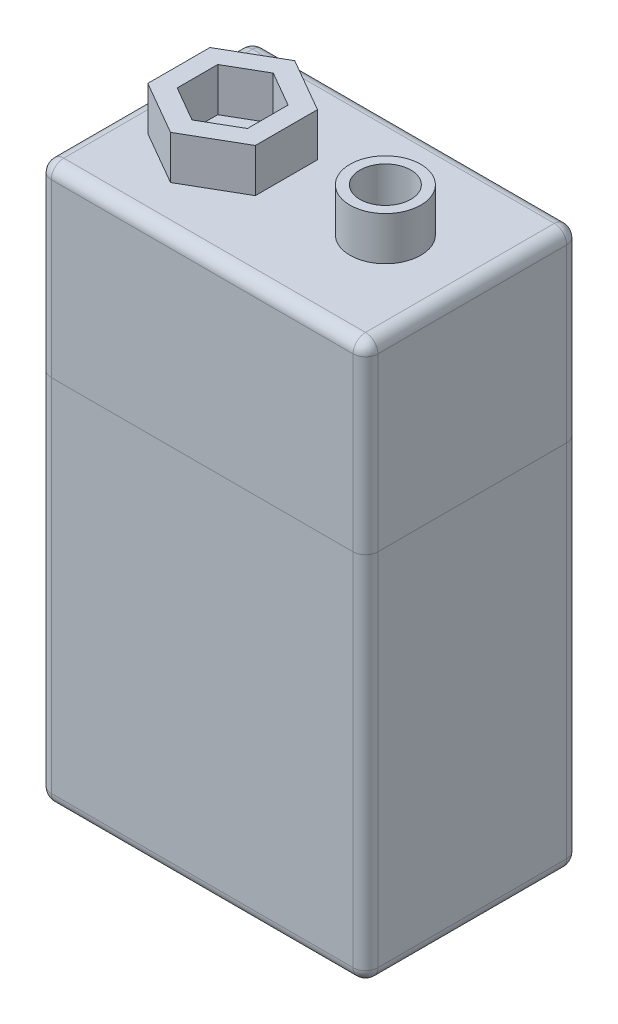
SolidWorks part; units mm, degrees
ref_plane "Alzado" through (0, 0, 0) normal (0, 0, 1) x (1, 0, 0)
ref_plane "Planta" through (0, 0, 0) normal (0, 1, 0) x (1, 0, 0)
ref_plane "Vista lateral" through (0, 0, 0) normal (1, 0, 0) x (0, 0, -1)
sketch "Croquis1" plane through (0, 0, 0) normal (0, 0, 1) x (1, 0, 0)
  line L1 (-13.15, 22.4) -> (13.15, 22.4)
  line L2 (-13.15, 22.4) -> (-13.15, -22.4)
  line L3 (-13.15, -22.4) -> (13.15, -22.4)
  line L4 (13.15, 22.4) -> (13.15, -22.4)
  line L5 (-13.15, 22.4) -> (13.15, -22.4) construction
  line L6 (-13.15, -22.4) -> (13.15, 22.4) construction
  point P0 (0, 0)
  dimension "D1" = 26.3
  dimension "D2" = 44.8
extrude "Saliente-Extruir1" add sketch "Croquis1" along normal blind 17.2
fillet "Redondeo1" radius 1 12 edges at (13.15, -22.4, 8.6) (0, -22.4, 0) (-13.15, -22.4, 8.6) (0, -22.4, 17.2) (0, 22.4, 0) (-13.15, 22.4, 8.6) (0, 22.4, 17.2) (13.15, 22.4, 8.6) (-13.15, 0, 0) (13.15, 0, 0) (13.15, 0, 17.2) (-13.15, 0, 17.2)
sketch "Croquis2" plane through (0, 0, 17.2) normal (0, 0, 1) x (1, 0, 0)
  line L0 (-13.15, -21.4) -> (-13.15, 21.4) construction
  line L1 (-13.15, 7.6) -> (13.15, 7.6)
  line L2 (-13.15, 7.6) -> (-13.15, -22.4)
  line L3 (-13.15, -22.4) -> (13.15, -22.4)
  line L4 (13.15, 7.6) -> (13.15, -22.4)
  line L5 (13.15, 21.4) -> (13.15, -21.4) construction
  line L6 (12.15, -22.4) -> (-12.15, -22.4) construction
  dimension "D1" = 30
split line "Línea de partición1"
sketch "Croquis3" plane through (0, 22.4, 0) normal (0, 1, 0) x (1, 0, 0)
  line L0 (12.15, -16.2) -> (12.15, -1) construction
  line L1 (13.15, -1) -> (13.15, -16.2) construction
  line L2 (-13.15, -16.2) -> (-13.15, -1) construction
  line L3 (-1.8199, -11.1) -> (-1.8199, -6.1)
  line L4 (-1.8199, -6.1) -> (-6.15, -3.6)
  line L5 (-6.15, -3.6) -> (-10.4801, -6.1)
  line L6 (-10.4801, -6.1) -> (-10.4801, -11.1)
  line L7 (-10.4801, -11.1) -> (-6.15, -13.6)
  line L8 (-6.15, -13.6) -> (-1.8199, -11.1)
  line L9 (-3.3199, -6.966) -> (-6.15, -5.3321)
  line L10 (-6.15, -5.3321) -> (-8.9801, -6.966)
  line L11 (-8.9801, -6.966) -> (-8.9801, -10.234)
  line L12 (-8.9801, -10.234) -> (-6.15, -11.8679)
  line L13 (-6.15, -11.8679) -> (-3.3199, -10.234)
  line L14 (-3.3199, -10.234) -> (-3.3199, -6.966)
  circle A0 centre (6.15, -8.6) radius 2.85
  circle A1 centre (6.15, -8.6) radius 2.05
  circle A2 centre (-6.15, -8.6) radius 4.3301 construction
  point P7 (12.15, -8.6)
  dimension "D1" = 5.7
  dimension "D3" = 7
  dimension "D4" = 7
  dimension "D5" = 5
  dimension "D2" = 0.8
  dimension "D6" = 1.5
extrude "Saliente-Extruir2" add sketch "Croquis3" along normal blind 3.5 separate body
